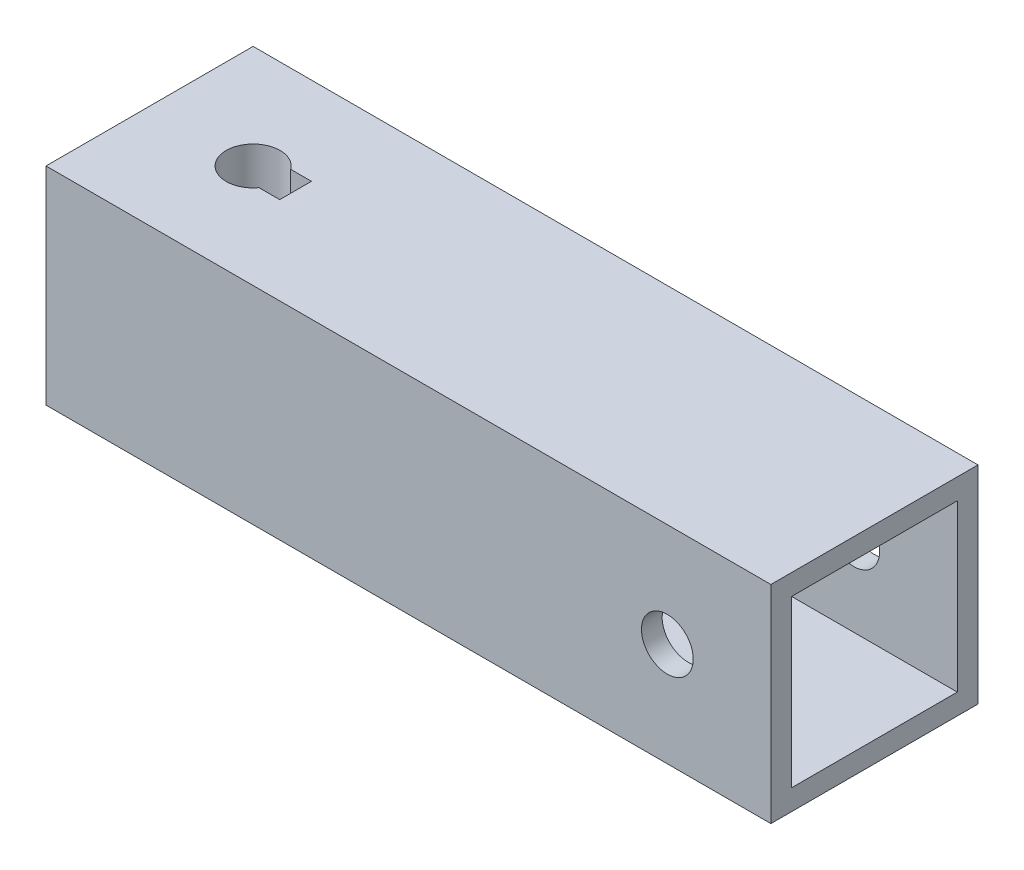
SolidWorks part; units mm, degrees
ref_plane "Front Plane" through (0, 0, 0) normal (0, 0, 1) x (1, 0, 0)
ref_plane "Top Plane" through (0, 0, 0) normal (0, 1, 0) x (1, 0, 0)
ref_plane "Right Plane" through (0, 0, 0) normal (1, 0, 0) x (0, 0, -1)
sketch "Sketch2" plane through (0, 0, 0) normal (0, 1, 0) x (1, 0, 0)
  line L1 (-70, -20) -> (70, -20)
  line L2 (-70, -20) -> (-70, 20)
  line L3 (-70, 20) -> (70, 20)
  line L4 (70, -20) -> (70, 20)
  line L5 (-70, -20) -> (70, 20) construction
  line L6 (-70, 20) -> (70, -20) construction
  circle A0 centre (-50, 0) radius 5.2
  point P0 (0, 0)
  point P8 (0, 0)
  point P9 (-70, 0)
  dimension "D3" = 10.4
  dimension "D1" = 40
  dimension "D2" = 140
  dimension "D4" = 20
extrude "Boss-Extrude1" add sketch "Sketch2" along normal blind 40
sketch "Sketch3" plane through (0, 0, 0) normal (0, 0, 1) x (1, 0, 0)
  line L0 (70, 40) -> (70, 0) construction
  line L1 (-70, 40) -> (70, 40) construction
  circle A0 centre (50, 20) radius 5
  dimension "D1" = 10
  dimension "D2" = 20
  dimension "D3" = 20
extrude "Cut-Extrude1" cut sketch "Sketch3" against normal through all both and the other way through all
sketch "Sketch5" plane through (0, 0, 0) normal (0, 1, 0) x (1, 0, 0)
  line L0 (-42.5, 20) -> (-42.5, 30)
  line L1 (-20.5662, 20) -> (-28.5048, 33.75)
  line L2 (70, 20) -> (-70, 20) construction
  line L3 (-42.5, 20) -> (-20.5662, 20)
  line L5 (-70, 20) -> (4.6794, 20)
  line L6 (-70, 20) -> (-70, 37.5)
  line L7 (-70, 37.5) -> (4.6794, 37.5)
  line L8 (4.6794, 20) -> (4.6794, 37.5)
  circle A0 centre (-35, 30) radius 4
  circle A1 centre (-35, 30) radius 7.5
  circle A2 centre (-65, 30) radius 4
  circle A3 centre (-50, 30) radius 4
  dimension "D1" = 8
  dimension "D2" = 15
  dimension "D6" = 8
  dimension "D8" = 8
  dimension "D3" = 60
  dimension "D4" = 10
  dimension "D5" = 15
  dimension "D7" = 15
  dimension "D9" = 20
sketch "Sketch7" plane through (0, 0, 0) normal (0, 1, 0) x (1, 0, 0)
  line L0 (-56.6, 0) -> (-43.8, 0) construction
  line L2 (-45.8, -3.0659) -> (-43.8, -3.0659)
  line L3 (-45.8, -3.0659) -> (-45.8, 3.0659)
  line L4 (-45.8, 3.0659) -> (-43.8, 3.0659)
  line L5 (-43.8, -3.0659) -> (-43.8, 3.0659)
  line L6 (-45.8, -3.0659) -> (-43.8, 3.0659) construction
  line L7 (-45.8, 3.0659) -> (-43.8, -3.0659) construction
  line L10 (-43.8, 3.0659) -> (-41.8, 3.0659)
  line L11 (-43.8, 3.0659) -> (-43.8, -3.0659)
  line L12 (-43.8, -3.0659) -> (-41.8, -3.0659)
  line L13 (-41.8, 3.0659) -> (-41.8, -3.0659)
  circle A0 centre (-50, 0) radius 5.2 construction
  point P4 (-44.8, 0)
  point P10 (-43.8, 0)
  dimension "D1" = 2
  dimension "D2" = 2
  dimension "D3" = 12.8
extrude "Cut-Extrude5" cut sketch "Sketch7" against normal through all and the other way through all contours L13 L10 L5 L12 | L2 L5 L4 L3
sketch "Sketch8" plane through (0, 0, 0) normal (1, 0, 0) x (0, 0, -1)
  line L0 (-20, 40) -> (20, 40) construction
  line L1 (-16, 4) -> (16, 4)
  line L2 (-16, 4) -> (-16, 36)
  line L3 (-16, 36) -> (16, 36)
  line L4 (16, 4) -> (16, 36)
  line L5 (-16, 4) -> (16, 36) construction
  line L6 (-16, 36) -> (16, 4) construction
  line L7 (20, 40) -> (20, 0) construction
  line L8 (-20, 0) -> (20, 0) construction
  point P0 (0, 20)
  dimension "D1" = 4
  dimension "D2" = 4
  dimension "D3" = 4
extrude "Cut-Extrude6" cut sketch "Sketch8" against normal blind 80 from surface at 70 starting at face at (70, 20, 0)
